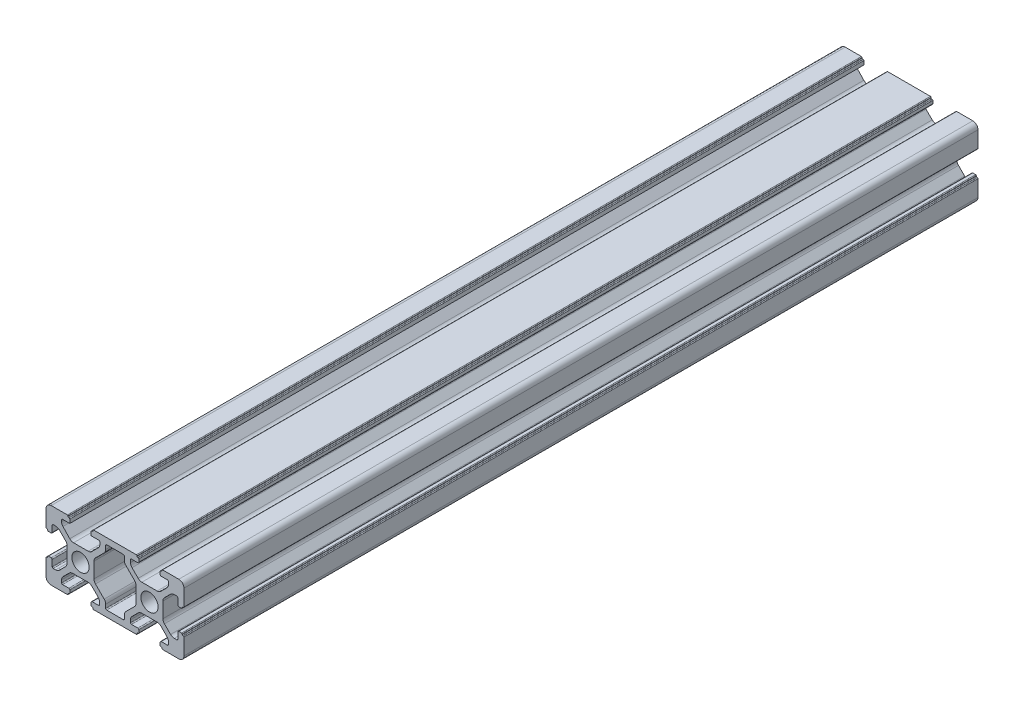
SolidWorks part; units mm, degrees
material "6063-O"
ref_plane "Front Plane" through (0, 0, 0) normal (0, 0, 1) x (1, 0, 0)
ref_plane "Top Plane" through (0, 0, 0) normal (0, 1, 0) x (1, 0, 0)
ref_plane "Right Plane" through (0, 0, 0) normal (1, 0, 0) x (0, 0, -1)
sketch "Sketch1" plane through (0, 0, 0) normal (0, 0, 1) x (1, 0, 0)
  line L0 (1.5, 0) -> (6.2, 0)
  line L1 (40, 1.5) -> (40, 6.2)
  line L2 (38.5, 20) -> (33.8, 20)
  line L3 (0, 18.5) -> (0, 13.8)
  line L4 (17.6, 1.8) -> (22.4, 1.8)
  line L5 (32.218, 13.9) -> (27.782, 13.9)
  line L6 (26.1, 12.218) -> (26.1, 7.782)
  line L7 (17.6, 18.2) -> (22.4, 18.2)
  line L8 (12.218, 13.9) -> (7.9864, 13.9)
  line L9 (6.1, 12.218) -> (6.1, 7.782)
  line L10 (7.782, 6.1) -> (12.218, 6.1)
  line L11 (13.9, 7.782) -> (13.9, 12.218)
  line L12 (27.782, 6.1) -> (32.218, 6.1)
  line L13 (33.9, 7.782) -> (33.9, 12.218)
  line L14 (26.7213, 14.3393) -> (24.9393, 16.1213)
  line L15 (33.2787, 14.3393) -> (35.0607, 16.1213)
  line L16 (34.3393, 13.2787) -> (36.1213, 15.0607)
  line L17 (25.6607, 6.7213) -> (23.1393, 4.2)
  line L18 (15.2, 1.8) -> (13.4, 1.8)
  line L19 (26.7213, 5.6607) -> (24.9393, 3.8787)
  line L20 (24.8, 1.8) -> (26.6, 1.8)
  line L21 (15.3, 18.2) -> (13.1, 18.2)
  line L22 (13.2787, 14.3393) -> (15.1607, 16.2213)
  line L23 (14.3393, 13.2787) -> (16.8607, 15.8)
  line L24 (5.6607, 6.7213) -> (3.8787, 4.9393)
  line L25 (6.7213, 5.6607) -> (4.9393, 3.8787)
  line L26 (6.897, 14.3689) -> (4.9106, 16.4674)
  line L27 (5.6607, 13.2787) -> (3.8787, 15.0607)
  line L28 (14.3393, 6.7213) -> (16.8607, 4.2)
  line L29 (13.2787, 5.6607) -> (15.0607, 3.8787)
  line L30 (24.8, 18.2) -> (26.6, 18.2)
  line L31 (25.6607, 13.2787) -> (23.1393, 15.8)
  line L32 (34.3393, 6.7213) -> (36.1213, 4.9393)
  line L33 (33.2787, 5.6607) -> (35.0607, 3.8787)
  line L34 (1.8, 15.2) -> (1.8, 13.4)
  line L35 (24.5, 2.1) -> (24.5, 2.818)
  line L36 (4.5, 2.1) -> (4.5, 2.818)
  line L37 (2.818, 4.5) -> (2.1, 4.5)
  line L38 (4.5, 17.9) -> (4.5, 17.4986)
  line L39 (2.818, 15.5) -> (2.1, 15.5)
  line L40 (15.6, 17.9) -> (15.6, 17.282)
  line L41 (15.5, 2.818) -> (15.5, 2.1)
  line L42 (38.2, 15.2) -> (38.2, 13.4)
  line L43 (35.5, 2.818) -> (35.5, 2.1)
  line L44 (37.182, 4.5) -> (37.9, 4.5)
  line L45 (35.5, 17.182) -> (35.5, 17.9)
  line L46 (37.182, 15.5) -> (37.9, 15.5)
  line L47 (17.3, 2.1) -> (17.3, 3.1393)
  line L48 (22.7, 2.1) -> (22.7, 3.1393)
  line L49 (17.3, 17.9) -> (17.3, 16.8607)
  line L50 (22.7, 17.9) -> (22.7, 16.8607)
  line L51 (24.5, 17.9) -> (24.5, 17.182)
  line L52 (6.9, 19.3) -> (6.9, 18.2)
  line L53 (13.1, 19.3) -> (13.1, 18.2)
  line L54 (6.9, 1.5) -> (6.9, 0.7)
  line L55 (13.1, 1.5) -> (13.1, 0.7)
  line L56 (13.8, 0) -> (26.2, 0)
  line L57 (6.6, 1.8) -> (4.8, 1.8)
  line L58 (6.9, 18.2) -> (4.8, 18.2)
  line L59 (6.2, 20) -> (1.5, 20)
  line L60 (39.3, 6.9) -> (38.5, 6.9)
  line L61 (39.3, 13.1) -> (38.5, 13.1)
  line L62 (1.5, 13.1) -> (0.7, 13.1)
  line L63 (1.5, 6.9) -> (0.7, 6.9)
  line L64 (0, 6.2) -> (0, 1.5)
  line L65 (1.8, 6.6) -> (1.8, 4.8)
  line L66 (38.2, 6.6) -> (38.2, 4.8)
  line L67 (40, 13.8) -> (40, 18.5)
  line L68 (33.1, 19.3) -> (33.1, 18.5)
  line L69 (26.9, 19.3) -> (26.9, 18.5)
  line L70 (26.9, 1.5) -> (26.9, 0.7)
  line L71 (33.1, 1.5) -> (33.1, 0.7)
  line L72 (33.8, 0) -> (38.5, 0)
  line L73 (33.4, 1.8) -> (35.2, 1.8)
  line L74 (26.2, 20) -> (13.8, 20)
  line L75 (33.4, 18.2) -> (35.2, 18.2)
  line L76 (6.7, 0.5) -> (6.6, 0.5)
  line L77 (6.4, 0.3) -> (6.4, 0.2)
  line L78 (13.3, 0.5) -> (13.4, 0.5)
  line L79 (13.6, 0.3) -> (13.6, 0.2)
  line L80 (26.7, 0.5) -> (26.6, 0.5)
  line L81 (26.4, 0.3) -> (26.4, 0.2)
  line L82 (33.3, 0.5) -> (33.4, 0.5)
  line L83 (33.6, 0.3) -> (33.6, 0.2)
  line L85 (6.4, 19.8) -> (6.4, 19.7)
  line L86 (6.6, 19.5) -> (6.7, 19.5)
  line L87 (13.6, 19.8) -> (13.6, 19.7)
  line L88 (13.4, 19.5) -> (13.3, 19.5)
  line L89 (26.4, 19.8) -> (26.4, 19.7)
  line L90 (26.6, 19.5) -> (26.7, 19.5)
  line L91 (33.6, 19.8) -> (33.6, 19.7)
  line L92 (33.4, 19.5) -> (33.3, 19.5)
  line L93 (0.5, 13.3) -> (0.5, 13.4)
  line L94 (0.3, 13.6) -> (0.2, 13.6)
  line L95 (0.5, 6.7) -> (0.5, 6.6)
  line L96 (0.3, 6.4) -> (0.2, 6.4)
  line L97 (39.5, 13.3) -> (39.5, 13.4)
  line L98 (39.7, 13.6) -> (39.8, 13.6)
  line L99 (39.5, 6.7) -> (39.5, 6.6)
  line L100 (39.7, 6.4) -> (39.8, 6.4)
  circle A0 centre (10, 10) radius 2.5
  circle A1 centre (30, 10) radius 2.5
  arc A2 (38.5, 0) -> (40, 1.5) centre (38.5, 1.5) ccw
  arc A3 (40, 18.5) -> (38.5, 20) centre (38.5, 18.5) ccw
  arc A4 (1.5, 0) -> (0, 1.5) centre (1.5, 1.5) cw
  arc A5 (1.5, 20) -> (0, 18.5) centre (1.5, 18.5) ccw
  arc A6 (26.7213, 5.6607) -> (27.782, 6.1) centre (27.782, 4.6) cw
  arc A7 (32.218, 6.1) -> (33.2787, 5.6607) centre (32.218, 4.6) cw
  arc A8 (33.9, 7.782) -> (34.3393, 6.7213) centre (35.4, 7.782) ccw
  arc A9 (33.2787, 14.3393) -> (32.218, 13.9) centre (32.218, 15.4) cw
  arc A10 (14.3393, 6.7213) -> (13.9, 7.782) centre (15.4, 7.782) cw
  arc A11 (14.3393, 13.2787) -> (13.9, 12.218) centre (15.4, 12.218) ccw
  arc A12 (25.6607, 6.7213) -> (26.1, 7.782) centre (24.6, 7.782) ccw
  arc A13 (26.1, 12.218) -> (25.6607, 13.2787) centre (24.6, 12.218) ccw
  arc A14 (27.782, 13.9) -> (26.7213, 14.3393) centre (27.782, 15.4) cw
  arc A15 (5.6607, 13.2787) -> (6.1, 12.218) centre (4.6, 12.218) cw
  arc A16 (5.6607, 6.7213) -> (6.1, 7.782) centre (4.6, 7.782) ccw
  arc A17 (13.2787, 5.6607) -> (12.218, 6.1) centre (12.218, 4.6) ccw
  arc A18 (6.7213, 5.6607) -> (7.782, 6.1) centre (7.782, 4.6) cw
  arc A19 (13.2787, 14.3393) -> (12.218, 13.9) centre (12.218, 15.4) cw
  arc A20 (6.897, 14.3689) -> (7.9864, 13.9) centre (7.9864, 15.4) ccw
  arc A21 (36.1213, 4.9393) -> (37.182, 4.5) centre (37.182, 6) ccw
  arc A22 (36.1213, 15.0607) -> (37.182, 15.5) centre (37.182, 14) cw
  arc A23 (35.0607, 16.1213) -> (35.5, 17.182) centre (34, 17.182) ccw
  arc A24 (24.5, 17.182) -> (24.9393, 16.1213) centre (26, 17.182) ccw
  arc A25 (22.7, 16.8607) -> (23.1393, 15.8) centre (24.2, 16.8607) ccw
  arc A26 (17.3, 16.8607) -> (16.8607, 15.8) centre (15.8, 16.8607) cw
  arc A27 (4.9106, 16.4674) -> (4.5, 17.4986) centre (6, 17.4986) cw
  arc A28 (15.6, 17.282) -> (15.1607, 16.2213) centre (14.1, 17.282) cw
  arc A29 (3.8787, 15.0607) -> (2.818, 15.5) centre (2.818, 14) ccw
  arc A30 (3.8787, 4.9393) -> (2.818, 4.5) centre (2.818, 6) cw
  arc A31 (4.9393, 3.8787) -> (4.5, 2.818) centre (6, 2.818) ccw
  arc A32 (35.0607, 3.8787) -> (35.5, 2.818) centre (34, 2.818) cw
  arc A33 (24.9393, 3.8787) -> (24.5, 2.818) centre (26, 2.818) ccw
  arc A34 (22.7, 3.1393) -> (23.1393, 4.2) centre (24.2, 3.1393) cw
  arc A35 (17.3, 3.1393) -> (16.8607, 4.2) centre (15.8, 3.1393) ccw
  arc A36 (15.5, 2.818) -> (15.0607, 3.8787) centre (14, 2.818) ccw
  arc A37 (1.8, 6.6) -> (1.5, 6.9) centre (1.5, 6.6) ccw
  arc A38 (1.8, 13.4) -> (1.5, 13.1) centre (1.5, 13.4) cw
  arc A39 (17.6, 18.2) -> (17.3, 17.9) centre (17.6, 17.9) ccw
  arc A40 (22.4, 1.8) -> (22.7, 2.1) centre (22.4, 2.1) ccw
  arc A41 (17.6, 1.8) -> (17.3, 2.1) centre (17.6, 2.1) cw
  arc A42 (15.2, 1.8) -> (15.5, 2.1) centre (15.2, 2.1) ccw
  arc A43 (6.6, 1.8) -> (6.9, 1.5) centre (6.6, 1.5) cw
  arc A44 (13.4, 1.8) -> (13.1, 1.5) centre (13.4, 1.5) ccw
  arc A45 (24.8, 1.8) -> (24.5, 2.1) centre (24.8, 2.1) cw
  arc A46 (35.2, 1.8) -> (35.5, 2.1) centre (35.2, 2.1) ccw
  arc A47 (26.6, 1.8) -> (26.9, 1.5) centre (26.6, 1.5) cw
  arc A48 (33.4, 1.8) -> (33.1, 1.5) centre (33.4, 1.5) ccw
  arc A49 (26.9, 18.5) -> (26.6, 18.2) centre (26.6, 18.5) cw
  arc A50 (33.1, 18.5) -> (33.4, 18.2) centre (33.4, 18.5) ccw
  arc A51 (37.9, 4.5) -> (38.2, 4.8) centre (37.9, 4.8) ccw
  arc A52 (38.5, 13.1) -> (38.2, 13.4) centre (38.5, 13.4) cw
  arc A53 (38.5, 6.9) -> (38.2, 6.6) centre (38.5, 6.6) ccw
  arc A54 (38.2, 15.2) -> (37.9, 15.5) centre (37.9, 15.2) ccw
  arc A55 (35.2, 18.2) -> (35.5, 17.9) centre (35.2, 17.9) cw
  arc A56 (24.8, 18.2) -> (24.5, 17.9) centre (24.8, 17.9) ccw
  arc A57 (22.4, 18.2) -> (22.7, 17.9) centre (22.4, 17.9) cw
  arc A58 (15.3, 18.2) -> (15.6, 17.9) centre (15.3, 17.9) cw
  arc A59 (4.5, 17.9) -> (4.8, 18.2) centre (4.8, 17.9) cw
  arc A60 (1.8, 15.2) -> (2.1, 15.5) centre (2.1, 15.2) cw
  arc A61 (1.8, 4.8) -> (2.1, 4.5) centre (2.1, 4.8) ccw
  arc A62 (4.5, 2.1) -> (4.8, 1.8) centre (4.8, 2.1) ccw
  arc A63 (34.3393, 13.2787) -> (33.9, 12.218) centre (35.4, 12.218) ccw
  arc A64 (6.4, 0.2) -> (6.2, 0) centre (6.2, 0.2) cw
  arc A65 (6.6, 0.5) -> (6.4, 0.3) centre (6.6, 0.3) ccw
  arc A66 (6.7, 0.5) -> (6.9, 0.7) centre (6.7, 0.7) ccw
  arc A67 (13.6, 0.2) -> (13.8, 0) centre (13.8, 0.2) ccw
  arc A68 (13.4, 0.5) -> (13.6, 0.3) centre (13.4, 0.3) cw
  arc A69 (13.3, 0.5) -> (13.1, 0.7) centre (13.3, 0.7) cw
  arc A70 (26.4, 0.2) -> (26.2, 0) centre (26.2, 0.2) cw
  arc A71 (26.6, 0.5) -> (26.4, 0.3) centre (26.6, 0.3) ccw
  arc A72 (26.7, 0.5) -> (26.9, 0.7) centre (26.7, 0.7) ccw
  arc A73 (33.6, 0.2) -> (33.8, 0) centre (33.8, 0.2) ccw
  arc A74 (33.4, 0.5) -> (33.6, 0.3) centre (33.4, 0.3) cw
  arc A75 (33.3, 0.5) -> (33.1, 0.7) centre (33.3, 0.7) cw
  arc A76 (39.8, 6.4) -> (40, 6.2) centre (39.8, 6.2) cw
  arc A77 (39.5, 6.6) -> (39.7, 6.4) centre (39.7, 6.6) ccw
  arc A78 (39.5, 6.7) -> (39.3, 6.9) centre (39.3, 6.7) ccw
  arc A79 (39.5, 13.3) -> (39.3, 13.1) centre (39.3, 13.3) cw
  arc A80 (39.5, 13.4) -> (39.7, 13.6) centre (39.7, 13.4) cw
  arc A81 (39.8, 13.6) -> (40, 13.8) centre (39.8, 13.8) ccw
  arc A82 (33.3, 19.5) -> (33.1, 19.3) centre (33.3, 19.3) ccw
  arc A83 (33.6, 19.7) -> (33.4, 19.5) centre (33.4, 19.7) cw
  arc A84 (33.6, 19.8) -> (33.8, 20) centre (33.8, 19.8) cw
  arc A85 (26.7, 19.5) -> (26.9, 19.3) centre (26.7, 19.3) cw
  arc A86 (26.4, 19.7) -> (26.6, 19.5) centre (26.6, 19.7) ccw
  arc A87 (26.4, 19.8) -> (26.2, 20) centre (26.2, 19.8) ccw
  arc A88 (0.2, 6.4) -> (0, 6.2) centre (0.2, 6.2) ccw
  arc A89 (0.5, 6.6) -> (0.3, 6.4) centre (0.3, 6.6) cw
  arc A90 (0.5, 6.7) -> (0.7, 6.9) centre (0.7, 6.7) cw
  arc A91 (13.3, 19.5) -> (13.1, 19.3) centre (13.3, 19.3) ccw
  arc A92 (13.6, 19.7) -> (13.4, 19.5) centre (13.4, 19.7) cw
  arc A93 (13.6, 19.8) -> (13.8, 20) centre (13.8, 19.8) cw
  arc A94 (6.2, 20) -> (6.4, 19.8) centre (6.2, 19.8) cw
  arc A95 (6.7, 19.5) -> (6.9, 19.3) centre (6.7, 19.3) cw
  arc A96 (6.4, 19.7) -> (6.6, 19.5) centre (6.6, 19.7) ccw
  arc A97 (0.5, 13.3) -> (0.7, 13.1) centre (0.7, 13.3) ccw
  arc A98 (0.2, 13.6) -> (0, 13.8) centre (0.2, 13.8) cw
  arc A99 (0.5, 13.4) -> (0.3, 13.6) centre (0.3, 13.4) ccw
  point P87 (0, 0)
  point P178 (1.8, 6.9)
  point P181 (1.8, 13.1)
  point P186 (22.7, 1.8)
  point P193 (6.9, 1.8)
  point P204 (33.1, 1.8)
  point P209 (33.1, 18.2)
  point P216 (38.2, 6.9)
  point P243 (6.9, 0.5)
  point P248 (13.6, 0.5)
  point P257 (26.9, 0.5)
extrude "Boss-Extrude2" add sketch "Sketch1" along normal blind 230.2 contours A57 L7 A39 L49 A26 L23 A11 L11 A10 L28 A35 L47 A41 L4 A40 L48 A34 L17 A12 L6 A13 L31 A25 L50 | A0 | A1 | L59 A5 L3 A98 L94 A99 L93 A97 L62 A38 L34 A60 L39 A29 L27 A15 L9 A16 L24 A30 L37 A61 L65 A37 L63 A90 L95 A89 L96 A88 L64 A4 L0 A64 L77 A65 L76 A66 L54 A43 L57 A62 L36 A31 L25 A18 L10 A17 L29 A36 L41 A42 L18 A44 L55 A69 L78 A68 L79 A67 L56 A70 L81 A71 L80 A72 L70 A47 L20 A45 L35 A33 L19 A6 L12 A7 L33 A32 L43 A46 L73 A48 L71 A75 L82 A74 L83 A73 L72 A2 L1 A76 L100 A77 L99 A78 L60 A53 L66 A51 L44 A21 L32 A8 L13 A63 L16 A22 L46 A54 L42 A52 L61 A79 L97 A80 L98 A81 L67 A3 L2 A84 L91 A83 L92 A82 L68 A50 L75 A55 L45 A23 L15 A9 L5 A14 L14 A24 L51 A56 L30 A49 L69 A85 L90 A86 L89 A87 L74 A93 L87 A92 L88 A91 L53 L21 A58 L40 A28 L22 A19 L8 A20 L26 A27 L38 A59 L58 L52 A95 L86 A96 L85 A94
